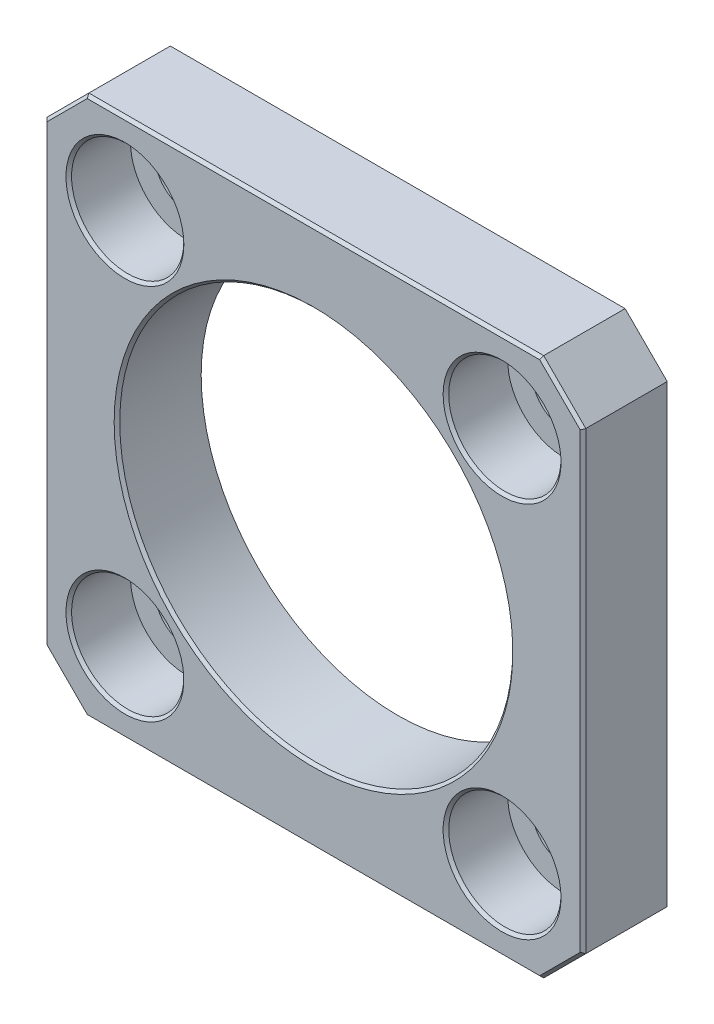
SolidWorks part; units mm, degrees
ref_plane "前基準面" through (0, 0, 0) normal (0, 0, 1) x (1, 0, 0)
ref_plane "上基準面" through (0, 0, 0) normal (0, 1, 0) x (1, 0, 0)
ref_plane "右基準面" through (0, 0, 0) normal (1, 0, 0) x (0, 0, -1)
sketch "草圖1" plane through (0, 0, 0) normal (0, 0, 1) x (1, 0, 0)
  line L0 (-19.2, 16.2) -> (-16.2, 19.2)
  line L1 (-16.2, -19.2) -> (16.2, -19.2)
  line L2 (-19.2, -16.2) -> (-19.2, 16.2)
  line L3 (-16.2, 19.2) -> (16.2, 19.2)
  line L4 (19.2, -16.2) -> (19.2, 16.2)
  line L5 (-19.2, -19.2) -> (19.2, 19.2) construction
  line L6 (-19.2, 19.2) -> (19.2, -19.2) construction
  line L7 (16.2, 19.2) -> (19.2, 16.2)
  line L8 (-16.2, -19.2) -> (-19.2, -16.2)
  line L9 (16.2, -19.2) -> (19.2, -16.2)
  circle A0 centre (0, 0) radius 14
  point P0 (0, 0)
  dimension "D3" = 28
  dimension "D1" = 38.4
  dimension "D2" = 38.4
extrude "填料-伸長1" add sketch "草圖1" along normal blind 6
sketch "草圖2" plane through (0, 0, 6) normal (0, 0, 1) x (1, 0, 0)
  line L0 (0, 0) -> (-22.7361, 0) construction
  line L1 (0, 0) -> (-21.2277, 21.2277) construction
  circle A0 centre (0, 0) radius 19 construction
  dimension "D1" = 38
  dimension "D2" = 45
hole_wizard "M4 六角承窩頭蓋螺釘的柱孔3" positions "草圖9" profile "草圖10" counterbore size "M4" standard "ISO" end condition through all
sketch "草圖9" plane through (0, 0, 6) normal (0, 0, 1) x (1, 0, 0)
  line L0 (0, 0) -> (-21.2277, 21.2277) construction
  circle A0 centre (0, 0) radius 19 construction
  point P0 (-13.435, 13.435)
sketch "草圖10" plane through (-13.435, 13.435, 6) normal (1, 0, 0) x (0, -1, 0)
  line L0 (0, 0) -> (0, 6)
  line L1 (0, 6) -> (2.25, 6)
  line L3 (2.25, 6) -> (2.25, 4.4)
  line L4 (2.25, 4.4) -> (4, 4.4)
  line L5 (4, 4.4) -> (4, 0)
  line L7 (4, 0) -> (0, 0)
  line L11 (0, -6.35) -> (0, 107.95) construction
  dimension "貫穿孔直徑" = 4.5
  dimension "貫穿孔深度" = 6
  dimension "柱孔直徑" = 8
  dimension "柱孔深度" = 4.4
pattern_circular "環狀複製排列1" count 4 over 360 about axis through (0, 0, 0) along (0, 0, 1) of "M4 六角承窩頭蓋螺釘的柱孔3"
chamfer "導角1" distance 0.2 angle 45 13 edges at (14, 0, 6) (17.435, 13.435, 6) (17.435, -13.435, 6) (-9.435, -13.435, 6) (-9.435, 13.435, 6) (-17.7, -17.7, 6) (-19.2, 0, 6) (-17.7, 17.7, 6) (0, -19.2, 6) (17.7, -17.7, 6) (19.2, 0, 6) (17.7, 17.7, 6) (0, 19.2, 6)
